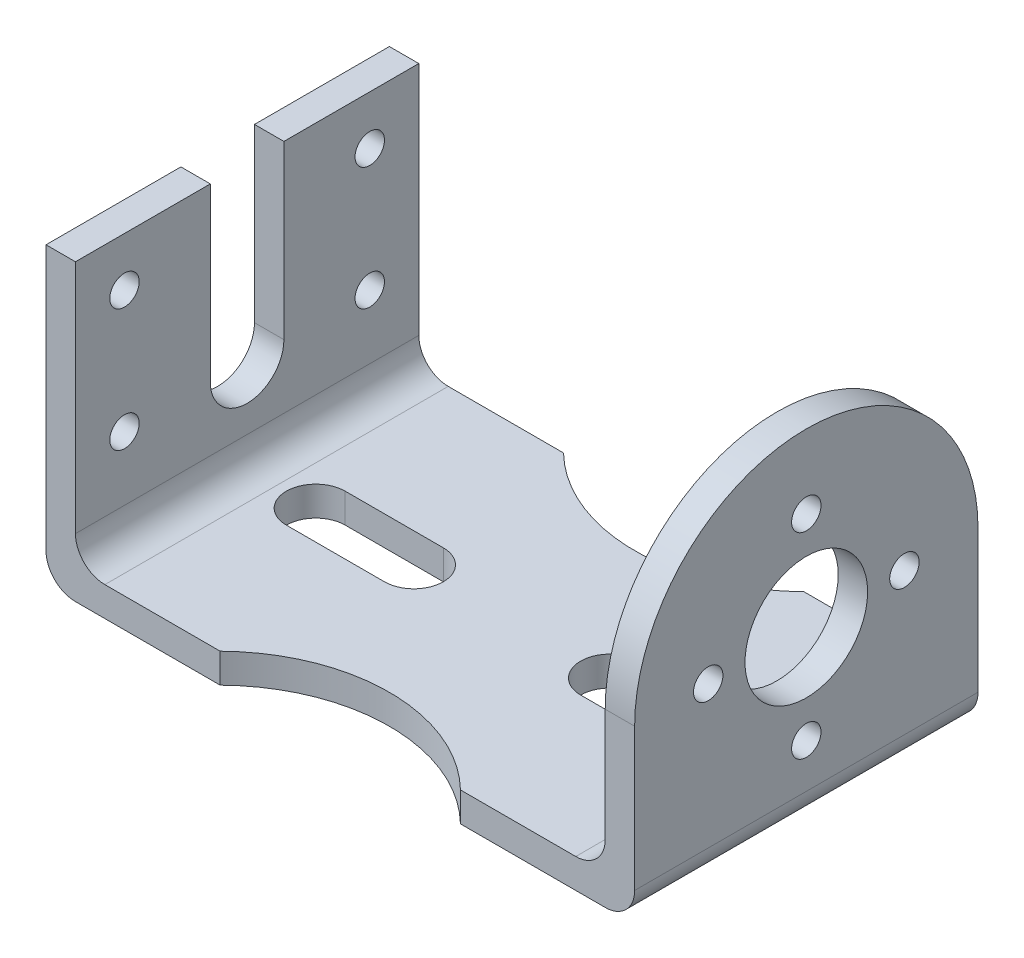
SolidWorks part; units mm, degrees
ref_plane "Front Plane" through (0, 0, 0) normal (0, 0, 1) x (1, 0, 0)
ref_plane "Top Plane" through (0, 0, 0) normal (0, 1, 0) x (1, 0, 0)
ref_plane "Right Plane" through (0, 0, 0) normal (1, 0, 0) x (0, 0, -1)
sketch "Sketch1" plane through (0, 0, 0) normal (0, 0, 1) x (1, 0, 0)
  line L0 (-54, 0) -> (54, 0)
  line L1 (60, 6) -> (60, 60)
  line L2 (-60, 6) -> (-60, 60)
  line L3 (-60, 60) -> (-54, 60)
  line L4 (-54, 60) -> (-54, 12)
  line L5 (-48, 6) -> (48, 6)
  line L6 (54, 12) -> (54, 60)
  line L7 (54, 60) -> (60, 60)
  arc A0 (48, 6) -> (54, 12) centre (48, 12) ccw
  arc A1 (-54, 12) -> (-48, 6) centre (-48, 12) ccw
  arc A2 (-54, 0) -> (-60, 6) centre (-54, 6) cw
  arc A3 (54, 0) -> (60, 6) centre (54, 6) ccw
  point P4 (0, 0)
  point P17 (-60, 0)
  point P20 (60, 0)
  dimension "D7" = 6
  dimension "D8" = 6
  dimension "D1" = 120
  dimension "D2" = 60
  dimension "D3" = 60
  dimension "D4" = 6
  dimension "D5" = 6
  dimension "D6" = 6
extrude "BasePlateExtrude" add sketch "Sketch1" against normal blind 70
sketch "Sketch2" plane through (60, 0, 0) normal (1, 0, 0) x (0, 0, -1)
  line L0 (70, 0) -> (0, 0) construction
  line L1 (0, 6) -> (0, 60) construction
  line L2 (70, 6) -> (70, 60) construction
  line L3 (0, 35) -> (0, 60)
  line L4 (0, 60) -> (10.5051, 60)
  line L5 (70, 60) -> (0, 60) construction
  line L6 (70, 35) -> (70, 60)
  line L7 (70, 60) -> (59.4949, 60)
  arc A0 (70, 35) -> (59.4949, 60) centre (35, 35) ccw
  arc A1 (10.5051, 60) -> (0, 35) centre (35, 35) ccw
  point P0 (35, 35)
  dimension "D1" = 35
  dimension "D2" = 35
extrude "FeatureOp1" cut sketch "Sketch2" against normal blind 33
sketch "Sketch3" plane through (60, 0, 0) normal (1, 0, 0) x (0, 0, -1)
  line L2 (10.5051, 60) -> (59.4949, 60)
  arc A0 (59.4949, 60) -> (10.5051, 60) centre (35, 35) ccw
  point P0 (35, 35)
extrude "FeatureOp2" add sketch "Sketch3" against normal blind 6
sketch "Sketch4" plane through (60, 0, 0) normal (1, 0, 0) x (0, 0, -1)
  circle A0 centre (35, 35) radius 12.5
  point P0 (35, 35)
extrude "FeatureOp3" cut sketch "Sketch4" against normal blind 16
sketch "Sketch5" plane through (60, 0, 0) normal (1, 0, 0) x (0, 0, -1)
  circle A1 centre (35, 55) radius 3
  circle A2 centre (55, 35) radius 3
  circle A3 centre (35, 15) radius 3
  circle A4 centre (15, 35) radius 3
  point P14 (35, 35)
  dimension "D1" = 4
extrude "FeatureOp4" cut sketch "Sketch5" against normal blind 16
sketch "Sketch6" plane through (-60, 0, 0) normal (-1, 0, 0) x (0, 0, 1)
  line L0 (-70, 0) -> (0, 0) construction
  line L1 (-42.5, 60) -> (-27.5, 60)
  line L2 (-70, 60) -> (0, 60) construction
  line L4 (-27.5, 60) -> (-27.5, 25)
  line L6 (-42.5, 25) -> (-42.5, 60)
  line L7 (-70, 60) -> (-70, 6) construction
  line L8 (0, 60) -> (0, 6) construction
  arc A0 (-42.5, 25) -> (-27.5, 25) centre (-35, 25) ccw
  circle A1 centre (-60, 50) radius 3
  circle A2 centre (-60, 25) radius 3
  circle A3 centre (-10, 50) radius 3
  circle A4 centre (-10, 25) radius 3
  point P0 (-35, 35)
  point P9 (-35, 60)
  dimension "D7" = 10
  dimension "D1" = 35
  dimension "D2" = 35
  dimension "D3" = 27.5
  dimension "D4" = 27.5
  dimension "D5" = 15
  dimension "D6" = 35
  dimension "D8" = 10
  dimension "D9" = 10
  dimension "D10" = 10
  dimension "D11" = 25
  dimension "D12" = 25
extrude "FeatureOp5" cut sketch "Sketch6" against normal blind 16
sketch "Sketch7" plane through (0, 6, 0) normal (0, 1, 0) x (1, 0, 0)
  line L0 (0, 0) -> (0, 70) construction
  line L1 (48, 70) -> (-48, 70) construction
  line L2 (-40, 41) -> (-20, 41)
  line L3 (-20, 29) -> (-40, 29)
  line L4 (20, 29) -> (40, 29)
  line L5 (40, 41) -> (20, 41)
  line L6 (-24.4949, 0) -> (24.4949, 0)
  line L7 (48, 0) -> (-48, 0) construction
  line L8 (-20, 35) -> (20, 35) construction
  line L9 (-24.4949, 70) -> (24.4949, 70)
  arc A0 (-20, 29) -> (-20, 41) centre (-20, 35) ccw
  arc A1 (-40, 41) -> (-40, 29) centre (-40, 35) ccw
  arc A2 (40, 41) -> (40, 29) centre (40, 35) cw
  arc A3 (20, 29) -> (20, 41) centre (20, 35) cw
  arc A4 (24.4949, 0) -> (-24.4949, 0) centre (0, -25) ccw
  arc A5 (24.4949, 70) -> (-24.4949, 70) centre (0, 95) cw
  point P6 (-20, 35)
  point P7 (-40, 35)
  point P20 (40, 35)
  point P21 (20, 35)
  point P22 (0, 10)
  point P30 (0, 60)
  dimension "D3" = 10
  dimension "D1" = 20
  dimension "D2" = 20
extrude "FeatureOp6" cut sketch "Sketch7" against normal blind 16
